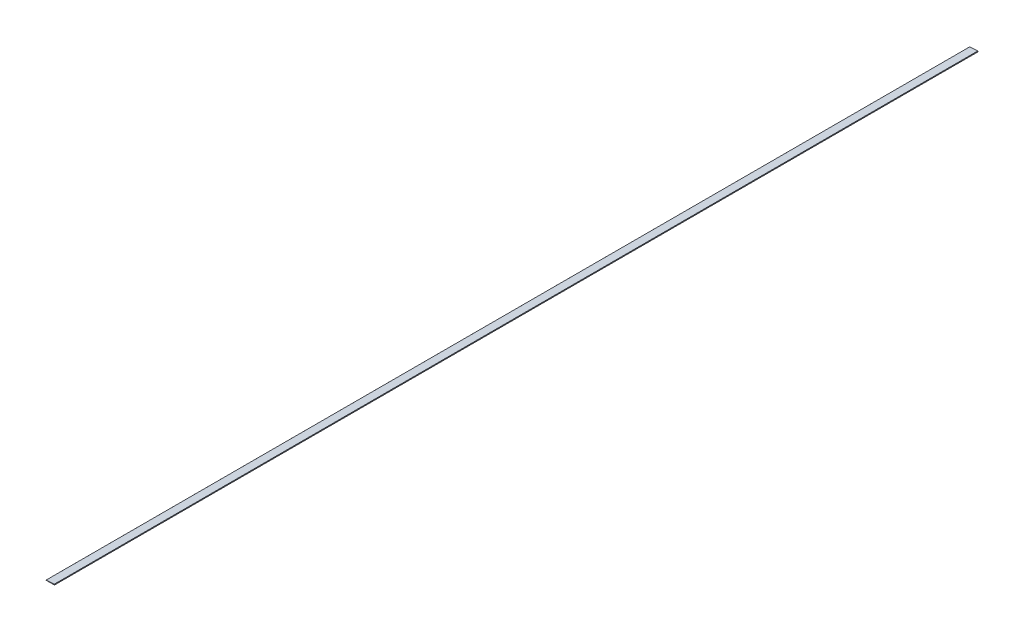
SolidWorks part; units mm, degrees
material "ASTM A500 Grade B Steel"
ref_plane "Front Plane" through (0, 0, 0) normal (0, 0, 1) x (1, 0, 0)
ref_plane "Top Plane" through (0, 0, 0) normal (0, 1, 0) x (1, 0, 0)
ref_plane "Right Plane" through (0, 0, 0) normal (1, 0, 0) x (0, 0, -1)
sketch "Sketch1" plane through (0, 0, 0) normal (0, 0, 1) x (1, 0, 0)
  line L0 (0, 0) -> (50.4141, 4.4107)
  line L1 (50.4141, 4.4107) -> (50.8, 0)
  line L2 (50.8, 0) -> (0, 0)
  dimension "D1" = 5
  dimension "D2" = 50.8
  dimension "D3" = 85
extrude "Boss-Extrude1" add sketch "Sketch1" against normal blind 5000
fillet "Fillet1" radius 0.2286 1 edges at (0, 0, -2500)
